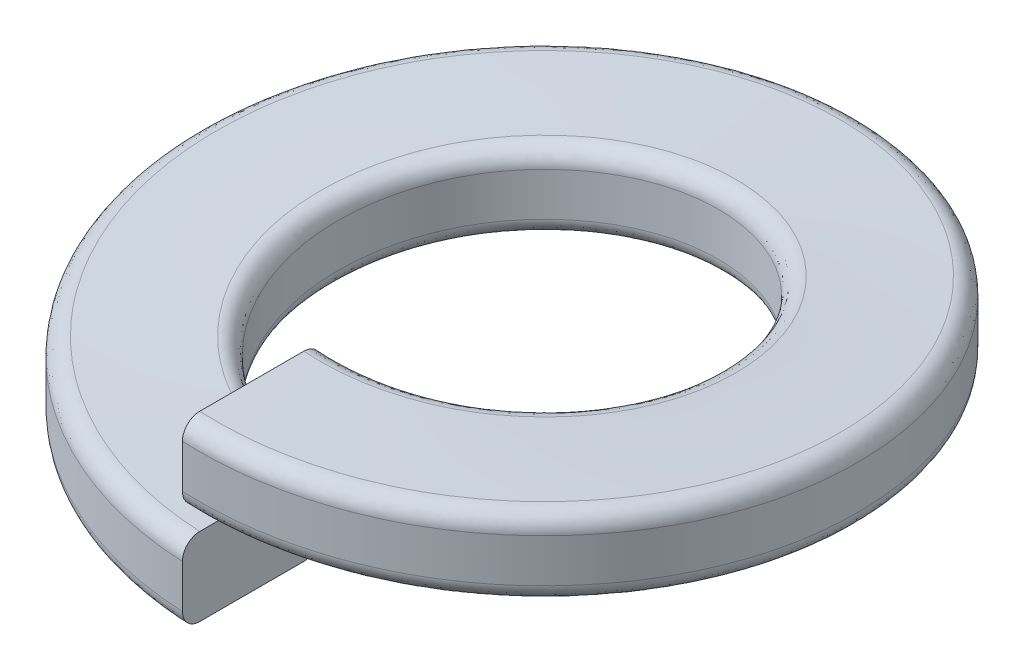
SolidWorks part; units mm, degrees
material "Cast Stainless Steel"
ref_plane "Front Plane" through (0, 0, 0) normal (0, 0, 1) x (1, 0, 0)
ref_plane "Top Plane" through (0, 0, 0) normal (0, 1, 0) x (1, 0, 0)
ref_plane "Right Plane" through (0, 0, 0) normal (1, 0, 0) x (0, 0, -1)
sketch "Sketch1" plane through (0, 0, 0) normal (0, 1, 0) x (1, 0, 0)
  circle A0 centre (0, 0) radius 2.2
  dimension "D1" = 4.4
curve "Helix/Spiral1" pitch 1.2 height 1.2 turns 1
sketch "Sketch2" plane through (0, 0, 0) normal (1, 0, 0) x (0, 0, -1)
  line L1 (-2.2, 0) -> (-3.8, 0)
  line L2 (-2.2, 0) -> (-2.2, 0.9)
  line L3 (-2.2, 0.9) -> (-3.8, 0.9)
  line L4 (-3.8, 0) -> (-3.8, 0.9)
  dimension "D1" = 1.6
  dimension "D2" = 0.9
sweep "Sweep1" add profiles "Sketch2" path "Helix/Spiral1"
fillet "Fillet1" radius 0.2 4 edges
sketch "Sketch3" plane through (0, 0, 0) normal (0, 1, 0) x (1, 0, 0)
  circle A0 centre (0, 0) radius 4.25
  dimension "D1" = 8.5
surface "Surface-Extrude1" sketch "Sketch3" parameters "D1"=0.5, "D19"=2
equation "\"d1\"= 4.4"
equation "\"d2\"= 7.6"
equation "\"h\"= 2.1"
equation "\"s\"= 0.9"
equation "\"D1@Sketch1\"=\"d1\""
equation "\"D3@Helix/Spiral1\"=\"h\"-\"s\""
equation "\"D1@Sketch2\"=(\"d2\"-\"d1\")/2"
equation "\"D2@Sketch2\"=\"s\""
equation "\"r\"= 0.2"
equation "\"D1@Fillet1\"=\"r\""
